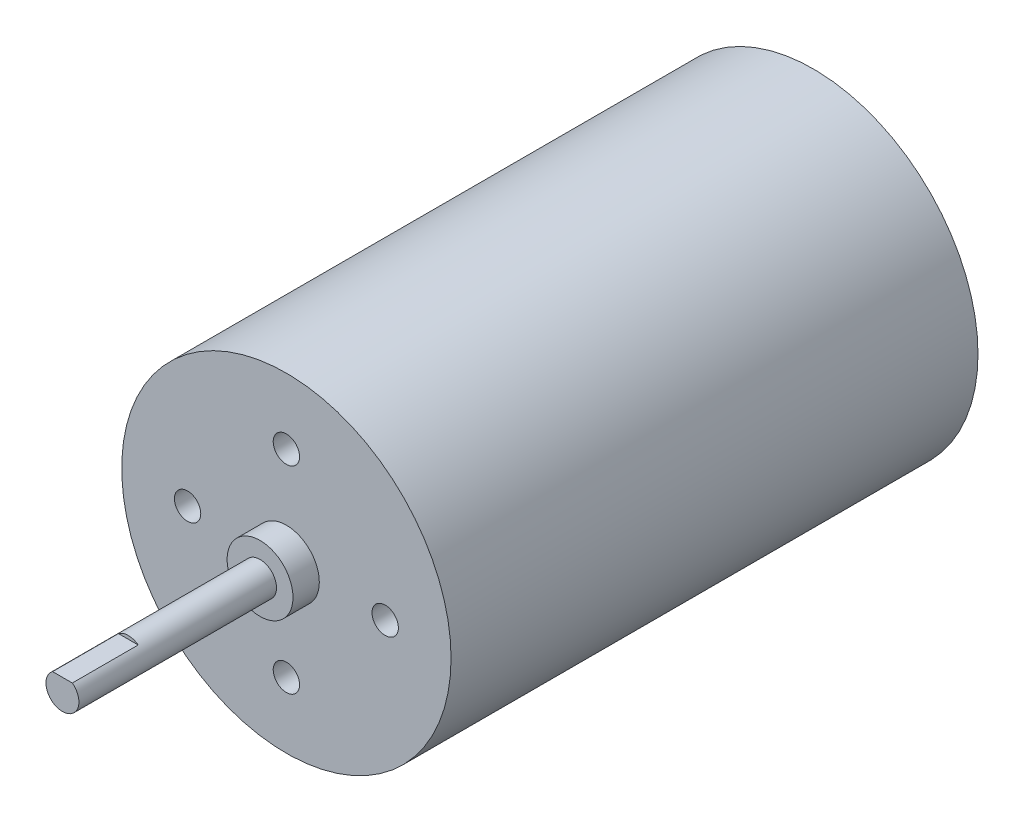
SolidWorks part; units mm, degrees
ref_plane "Front Plane" through (0, 0, 0) normal (0, 0, 1) x (1, 0, 0)
ref_plane "Top Plane" through (0, 0, 0) normal (0, 1, 0) x (1, 0, 0)
ref_plane "Right Plane" through (0, 0, 0) normal (1, 0, 0) x (0, 0, -1)
sketch "Sketch1" plane through (0, 0, 0) normal (0, 0, 1) x (1, 0, 0)
  circle A0 centre (0, 0) radius 15.875
  dimension "D1" = 31.75
extrude "Boss-Extrude1" add sketch "Sketch1" along normal blind 50.8
sketch "Sketch2" plane through (0, 0, 0) normal (0, 0, -1) x (-1, 0, 0)
  circle A0 centre (0, 0) radius 6.35
  dimension "D1" = 12.7
extrude "Boss-Extrude2" add sketch "Sketch2" along normal blind 6.35
sketch "Sketch3" plane through (0, 0, -6.35) normal (0, 0, -1) x (-1, 0, 0)
  circle A0 centre (0, 0) radius 1.5875
  dimension "D1" = 3.175
extrude "Boss-Extrude3" add sketch "Sketch3" along normal blind 3.175
sketch "Sketch4" plane through (0, 0, 50.8) normal (0, 0, 1) x (1, 0, 0)
  circle A0 centre (0, 0) radius 3.175
  dimension "D1" = 6.35
extrude "Boss-Extrude4" add sketch "Sketch4" along normal blind 2.54
sketch "Sketch5" plane through (0, 0, 53.34) normal (0, 0, 1) x (1, 0, 0)
  circle A0 centre (0, 0) radius 1.5875
  dimension "D1" = 3.175
extrude "Boss-Extrude5" add sketch "Sketch5" along normal blind 19.05
sketch "Sketch6" plane through (0, 0, 72.39) normal (0, 0, 1) x (1, 0, 0)
  line L0 (-0.9525, 1.27) -> (0.9525, 1.27)
  circle A0 centre (0, 0) radius 1.5875 construction
  circle A1 centre (0, 0) radius 1.5875 construction
  arc A2 (0.9525, 1.27) -> (-0.9525, 1.27) centre (0, 0) ccw
  circle M2 centre (0, 0) radius 1.5875
  dimension "D1" = 1.27
extrude "Cut-Extrude1" cut sketch "Sketch6" against normal blind 6.35 contours L0 M2
sketch "Sketch7" plane through (0, 0, 50.8) normal (0, 0, 1) x (1, 0, 0)
  circle A0 centre (0, 9.525) radius 1.27
  circle A1 centre (0, 0) radius 9.525 construction
  circle A2 centre (9.525, 0) radius 1.27
  circle A3 centre (0, -9.525) radius 1.27
  circle A4 centre (-9.525, 0) radius 1.27
  point P14 (0, 0)
  dimension "D1" = 19.05
  dimension "D2" = 2.54
  dimension "D3" = 4
extrude "Cut-Extrude2" cut sketch "Sketch7" against normal blind 8.89
